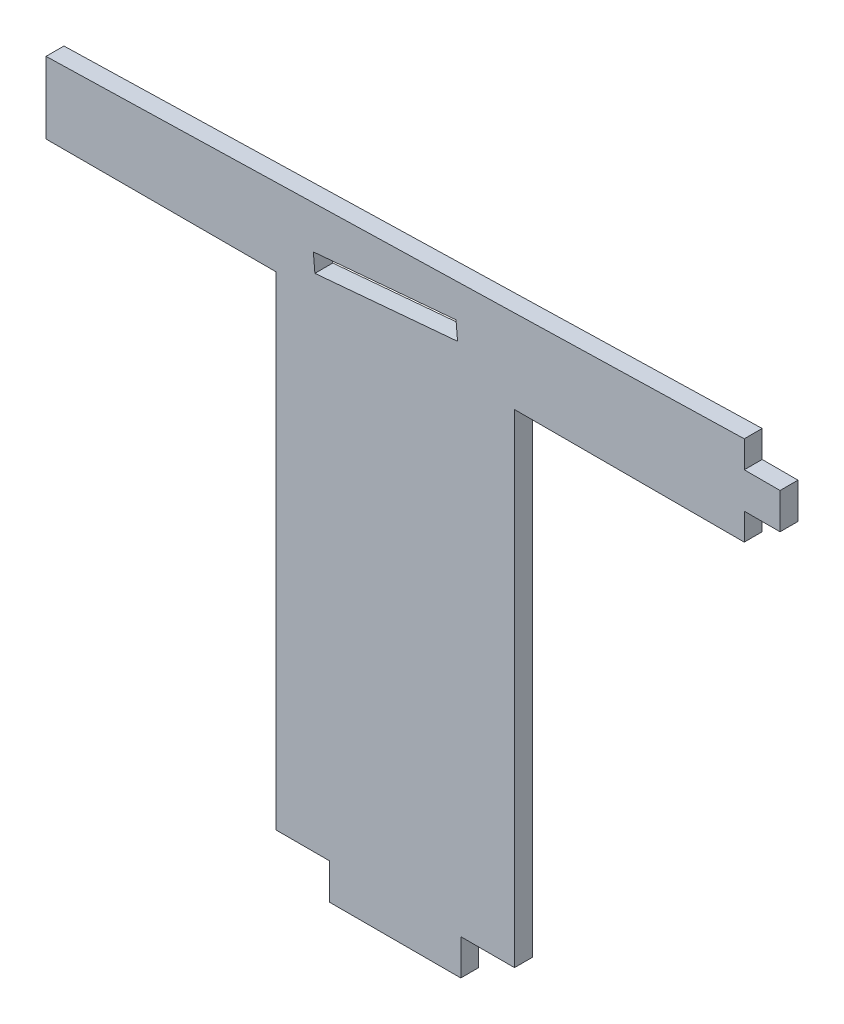
SolidWorks part; units mm, degrees
ref_plane "Front Plane" through (0, 0, 0) normal (0, 0, 1) x (1, 0, 0)
ref_plane "Top Plane" through (0, 0, 0) normal (0, 1, 0) x (1, 0, 0)
ref_plane "Right Plane" through (0, 0, 0) normal (1, 0, 0) x (0, 0, -1)
sketch "Sketch1" plane through (0, 0, 0) normal (0, 0, 1) x (1, 0, 0)
  line L0 (-78.5, 93) -> (-78.5, 81)
  line L1 (-78.5, 81) -> (-40, 81)
  line L2 (-40, 81) -> (-40, 0)
  line L3 (-40, 0) -> (0, 0)
  line L4 (0, 0) -> (0, 81)
  line L5 (0, 81) -> (38.5, 81)
  line L7 (38.5, 93) -> (-78.5, 93) construction
  line L8 (-78.5, 93) -> (38.5, 96)
  line L9 (38.5, 96) -> (38.5, 81)
  point P7 (-20, 0)
  point P9 (-20, 93)
  dimension "D1" = 117
  dimension "D2" = 12
  dimension "D3" = 40
  dimension "D4" = 93
  dimension "D5" = 3
extrude "Boss-Extrude1" add sketch "Sketch1" along normal blind 3
sketch "Sketch2" plane through (0, 0, 3) normal (0, 0, 1) x (1, 0, 0)
  line L0 (-33.71, 87.02) -> (-33.4485, 84.0314)
  line L1 (-33.4485, 84.0314) -> (-9.5399, 86.1232)
  line L2 (-9.5399, 86.1232) -> (-9.8013, 89.1117)
  line L3 (-9.8013, 89.1117) -> (-33.71, 87.02)
  line L4 (-78.5, 93) -> (-78.5, 81) construction
  line L5 (-33.71, 82.2014) -> (-33.71, 50082.2014) construction
  line L6 (-33.2208, 81.4288) -> (4324.5663, -49728.3061) construction
  line L8 (-78.5, 81) -> (-40, 81) construction
  point P2 (0, 0)
  dimension "D1" = 44.79
  dimension "D2" = 5
  dimension "D3" = 3
  dimension "D4" = 24
  dimension "D5" = 6.02
extrude "Cut-Extrude1" cut sketch "Sketch2" against normal through all
sketch "Sketch3" plane through (0, 0, 3) normal (0, 0, 1) x (1, 0, 0)
  line L0 (38.5, 81) -> (38.5, 96) construction
  line L1 (38.5, 91.5) -> (44.5, 91.5)
  line L2 (38.5, 91.5) -> (38.5, 85.5)
  line L3 (38.5, 85.5) -> (44.5, 85.5)
  line L4 (44.5, 91.5) -> (44.5, 85.5)
  line L5 (-40, 0) -> (0, 0) construction
  line L6 (-31, 0) -> (-9, 0)
  line L7 (-31, 0) -> (-31, -6)
  line L8 (-31, -6) -> (-9, -6)
  line L9 (-9, 0) -> (-9, -6)
  point P12 (-20, -6)
  point P13 (-20, 0)
  point P14 (38.5, 88.5)
  point P16 (38.5, 88.5)
  point P17 (0, 0)
  dimension "D1" = 9
  dimension "D2" = 6
  dimension "D3" = 6
extrude "Boss-Extrude2" add sketch "Sketch3" against normal through all
